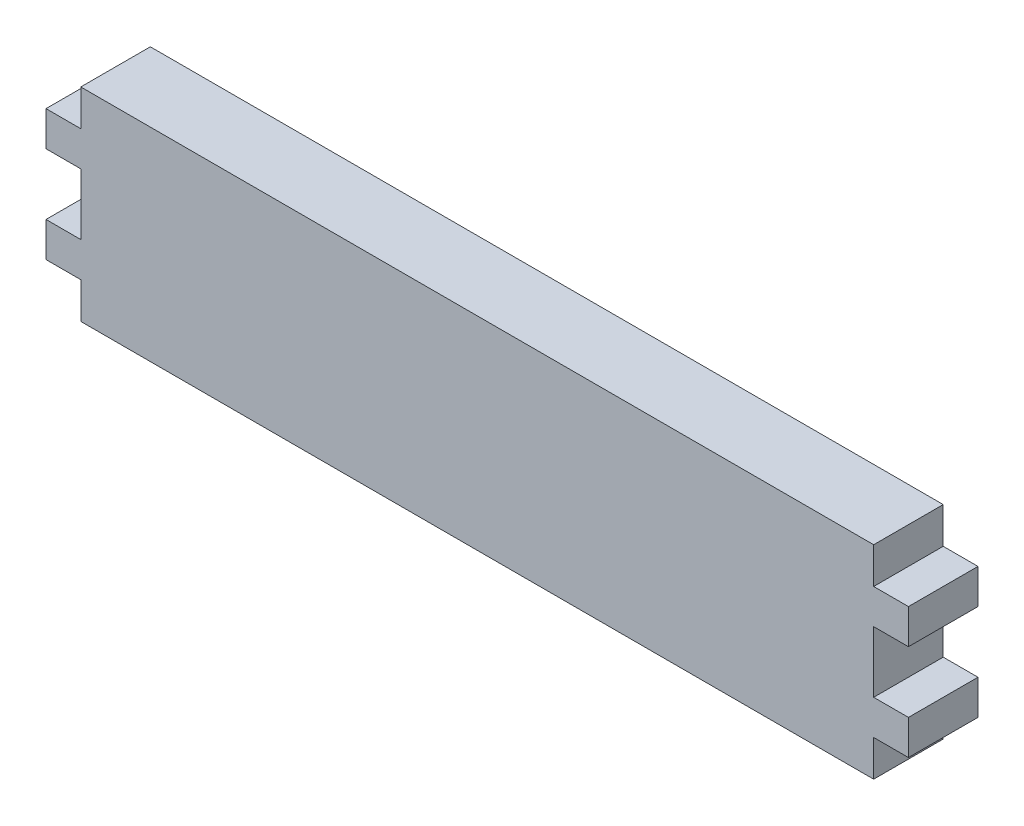
SolidWorks part; units mm, degrees
material "Balsa"
ref_plane "Front Plane" through (0, 0, 0) normal (0, 0, 1) x (1, 0, 0)
ref_plane "Top Plane" through (0, 0, 0) normal (0, 1, 0) x (1, 0, 0)
ref_plane "Right Plane" through (0, 0, 0) normal (1, 0, 0) x (0, 0, -1)
sketch "Sketch1" plane through (0, 0, 0) normal (0, 0, 1) x (1, 0, 0)
  line L0 (305.4123, -22.5272) -> (308.5873, -22.5272)
  line L1 (308.5873, -22.5272) -> (308.5873, -19.3522)
  line L3 (305.4123, -19.3522) -> (305.4123, -13.7642)
  line L4 (305.4123, -13.7642) -> (308.5873, -13.7642)
  line L5 (308.5873, -13.7642) -> (308.5873, -10.5892)
  line L6 (308.5873, -10.5892) -> (305.4123, -10.5892)
  line L7 (305.4123, -26.9092) -> (305.4123, -4.2789) construction
  line L8 (233.0223, -22.5272) -> (229.8473, -22.5272)
  line L9 (229.8473, -22.5272) -> (229.8473, -19.3522)
  line L10 (229.8473, -19.3522) -> (233.0223, -19.3522)
  line L11 (233.0223, -19.3522) -> (233.0223, -13.7642)
  line L12 (233.0223, -13.7642) -> (229.8473, -13.7642)
  line L13 (229.8473, -13.7642) -> (229.8473, -10.5892)
  line L14 (229.8473, -10.5892) -> (233.0223, -10.5892)
  line L15 (305.4123, -10.5892) -> (305.4123, -7.2872)
  line L16 (305.4123, -7.2872) -> (233.0223, -7.2872)
  line L17 (233.0223, -7.2872) -> (233.0223, -10.5892)
  line L18 (233.0223, -22.5272) -> (233.0223, -25.8292)
  line L19 (233.0223, -25.8292) -> (305.4123, -25.8292)
  line L20 (305.4123, -25.8292) -> (305.4123, -22.5272)
  line L21 (305.4123, -19.3522) -> (308.5873, -19.3522)
  point P18 (305.4123, -16.5582)
  point P19 (305.4123, -25.8292)
  point P20 (305.4123, -7.2872)
  dimension "D1" = 9.271
  dimension "D2" = 9.271
extrude "Boss-Extrude1" add sketch "Sketch1" along normal up to surface (6.35 mm away) contours L15 L16 L17 L14 L13 L12 L11 L10 L9 L8 L18 L19 L20 L0 L1 L21 L3 L4 L5 L6
